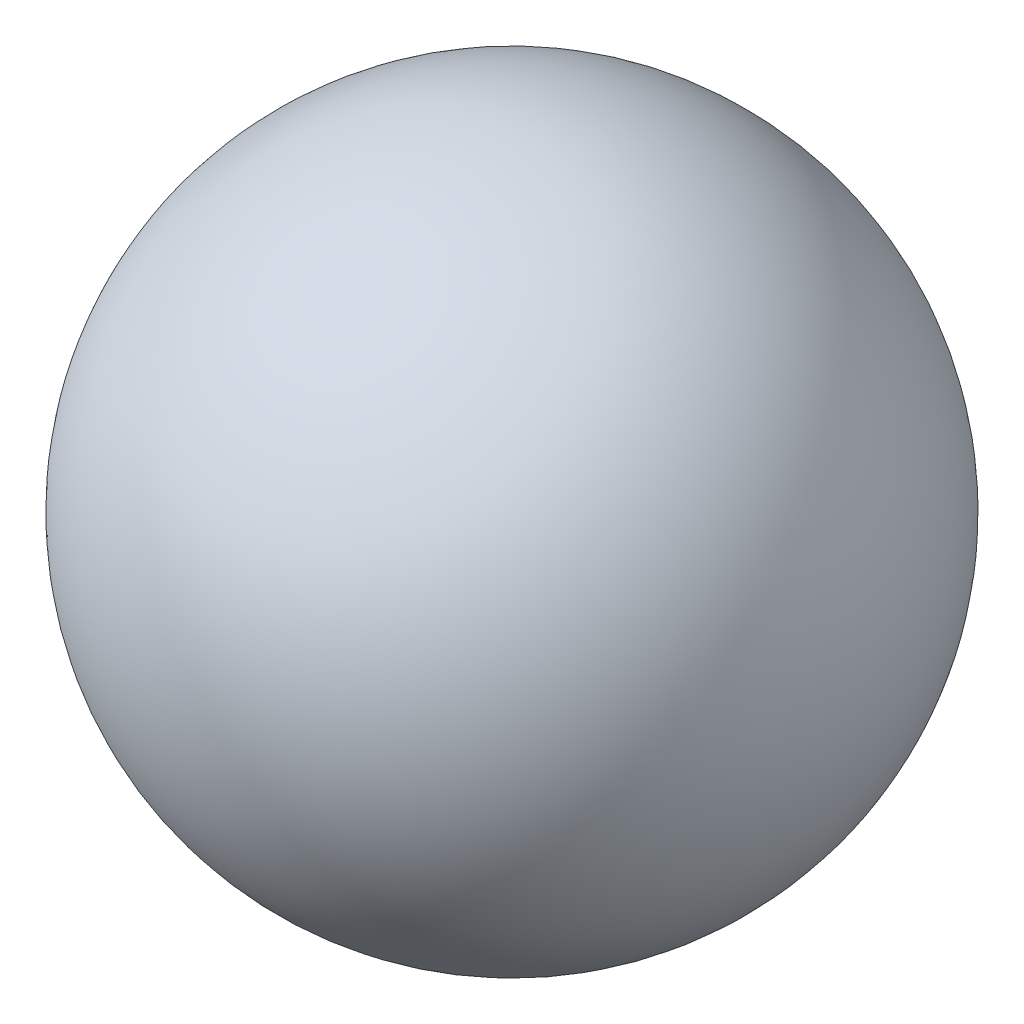
SolidWorks part; units mm, degrees
ref_plane "Front Plane" through (0, 0, 0) normal (0, 0, 1) x (1, 0, 0)
ref_plane "Top Plane" through (0, 0, 0) normal (0, 1, 0) x (1, 0, 0)
ref_plane "Right Plane" through (0, 0, 0) normal (1, 0, 0) x (0, 0, -1)
sketch "Sketch1" plane through (0, 0, 0) normal (0, 0, 1) x (1, 0, 0)
  line L0 (-88, 0) -> (-87, 0) construction
  line L1 (-87, 0) -> (87, 0) construction
  line L3 (0, 0) -> (0, 87) construction
  line L4 (0, 87) -> (0, 88) construction
  line L5 (-88, 0) -> (-87, 0)
  line L6 (88, 0) -> (87, 0) construction
  line L7 (88, 0) -> (87, 0)
  arc A0 (88, 0) -> (-88, 0) centre (0, 0) ccw
  arc A1 (87, 0) -> (-87, 0) centre (0, 0) ccw
revolve "Revolve1" add sketch "Sketch1" angle 360 about L1
